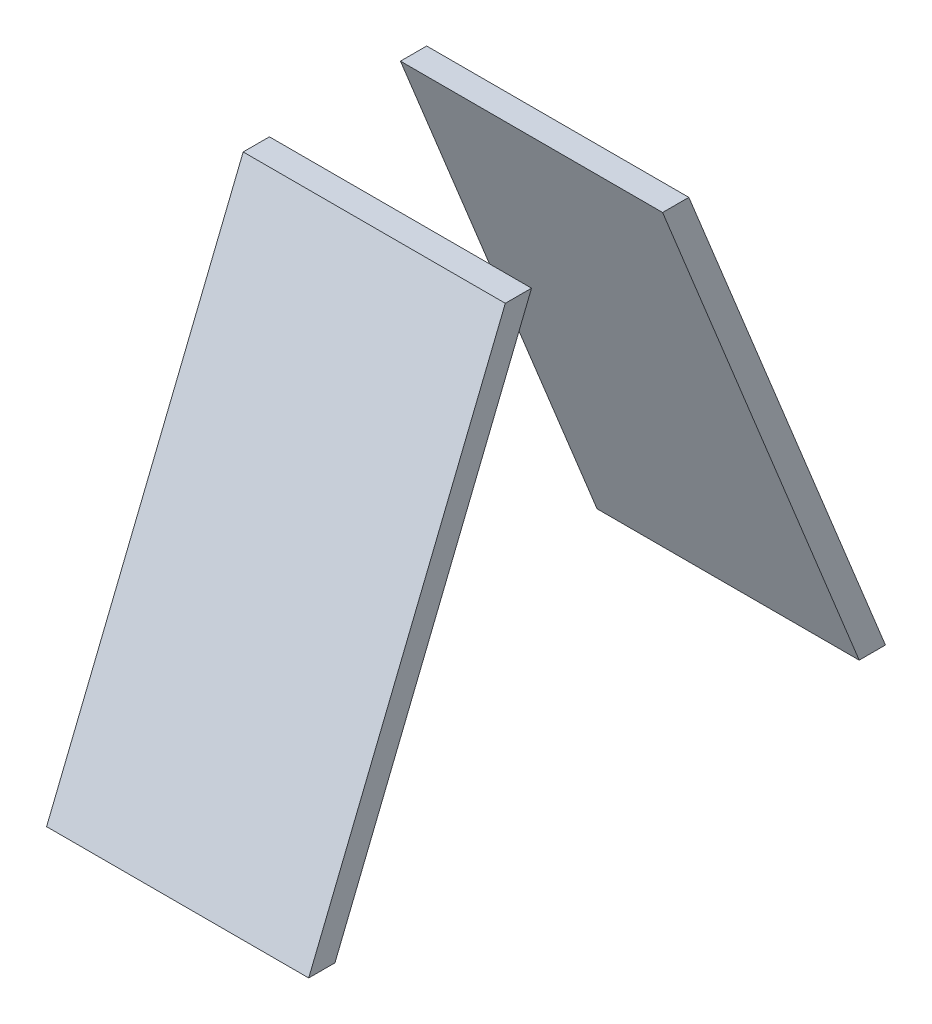
SolidWorks part; units mm, degrees
ref_plane "Front Plane" through (0, 0, 0) normal (0, 0, 1) x (1, 0, 0)
ref_plane "Top Plane" through (0, 0, 0) normal (0, 1, 0) x (1, 0, 0)
ref_plane "Right Plane" through (0, 0, 0) normal (1, 0, 0) x (0, 0, -1)
sketch "Sketch1" plane through (0, 0, 0) normal (1, 0, 0) x (0, 0, -1)
  line L0 (0, 0) -> (0, 50) construction
  line L1 (-25, 50) -> (25, 50) construction
  line L2 (-25, 50) -> (-100, -135.405)
  line L3 (-25, 50) -> (-35, 50)
  line L4 (-35, 50) -> (-110, -135.405)
  line L5 (-110, -135.405) -> (-100, -135.405)
  line L6 (110, -135.405) -> (100, -135.405)
  line L7 (35, 50) -> (110, -135.405)
  line L8 (25, 50) -> (35, 50)
  line L9 (25, 50) -> (100, -135.405)
  point P6 (0, 50)
  point P7 (0, 50)
  dimension "D1" = 50
  dimension "D2" = 50
  dimension "D3" = 200
  dimension "D4" = 10
  dimension "D5" = 200
extrude "Boss-Extrude1" add sketch "Sketch1" along normal blind 100
